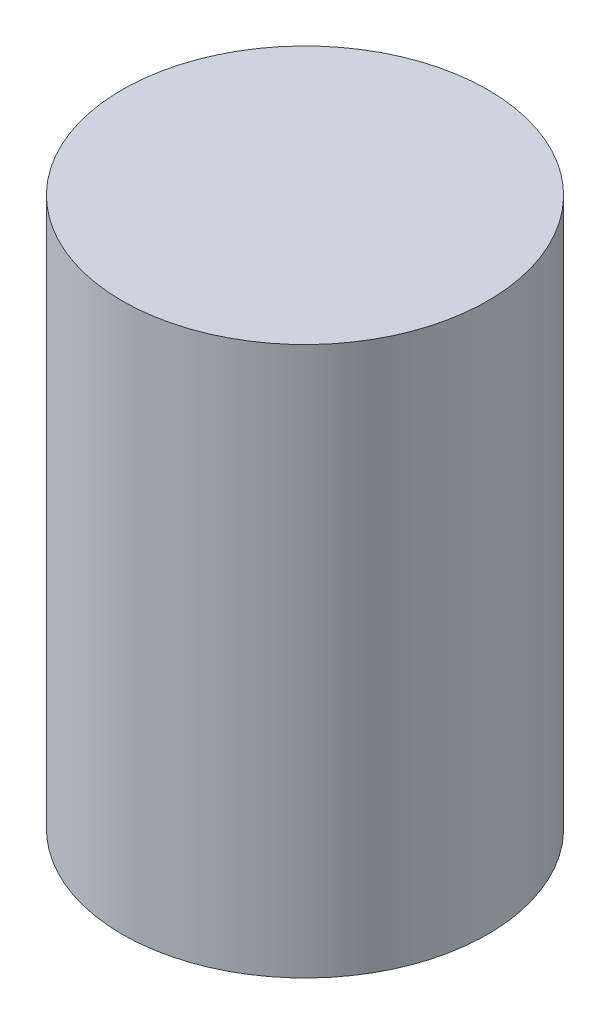
SolidWorks part; units mm, degrees
ref_plane "Front Plane" through (0, 0, 0) normal (0, 0, 1) x (1, 0, 0)
ref_plane "Top Plane" through (0, 0, 0) normal (0, 1, 0) x (1, 0, 0)
ref_plane "Right Plane" through (0, 0, 0) normal (1, 0, 0) x (0, 0, -1)
sketch "Sketch1" plane through (0, 0, 0) normal (0, 1, 0) x (1, 0, 0)
  circle A0 centre (0, 0) radius 1.27
  dimension "D1" = 2.54
extrude "Dowel" add sketch "Sketch1" along normal blind 3.81
